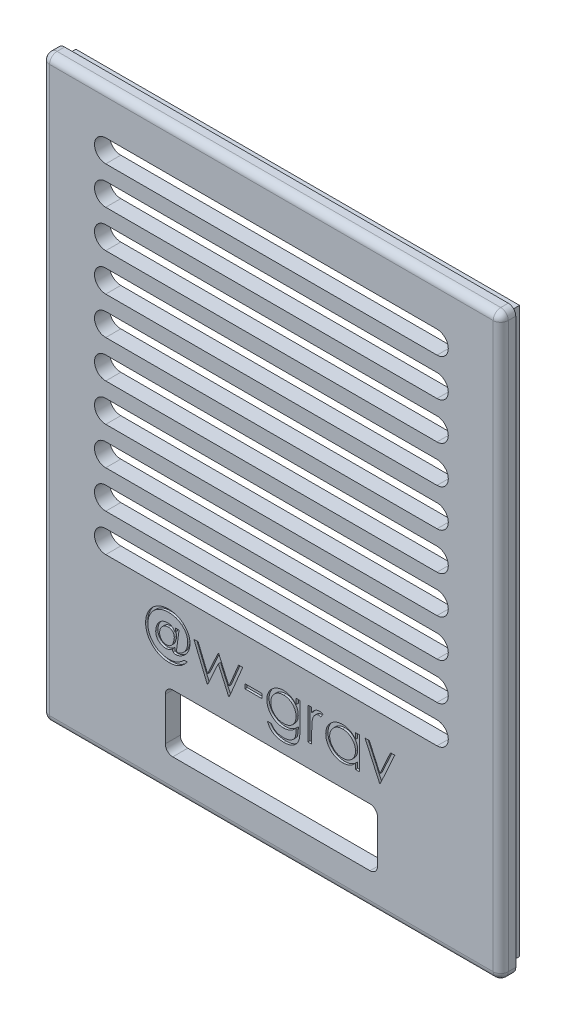
SolidWorks part; units mm, degrees
ref_plane "Спереди" through (0, 0, 0) normal (0, 0, 1) x (1, 0, 0)
ref_plane "Сверху" through (0, 0, 0) normal (0, 1, 0) x (1, 0, 0)
ref_plane "Справа" through (0, 0, 0) normal (1, 0, 0) x (0, 0, -1)
sketch "Эскиз1" plane through (0, 0, 0) normal (0, 0, 1) x (1, 0, 0)
  line L0 (-29.5, -37.5) -> (29.5, -37.5)
  line L1 (-29.5, -37.5) -> (-29.5, 37.5)
  line L2 (-29.5, 37.5) -> (29.5, 37.5)
  line L3 (29.5, -37.5) -> (29.5, 37.5)
  line L4 (-29.5, -37.5) -> (29.5, 37.5) construction
  line L5 (-29.5, 37.5) -> (29.5, -37.5) construction
  point P0 (0, 0)
extrude "Бобышка-Вытянуть1" add sketch "Эскиз1" along normal blind 2
sketch "Эскиз2" plane through (0, 0, 2) normal (0, 0, 1) x (1, 0, 0)
  line L1 (-29.5, -37.5) -> (29.5, -37.5)
  line L2 (-29.5, -37.5) -> (-29.5, 37.5)
  line L3 (-29.5, 37.5) -> (29.5, 37.5)
  line L4 (29.5, -37.5) -> (29.5, 37.5)
  line L5 (-29.5, -37.5) -> (29.5, 37.5) construction
  line L6 (-29.5, 37.5) -> (29.5, -37.5) construction
  point P0 (0, 0)
extrude "Вытянуть-Тонкостенный1" add sketch "Эскиз2" against normal blind 2 thin
fillet "Скругление1" radius 1 4 edges at (-30.5, -38.5, 1) (30.5, -38.5, 1) (30.5, 38.5, 1) (-30.5, 38.5, 1)
sketch "Эскиз5" plane through (0, 0, 0) normal (0, 0, -1) x (-1, 0, 0)
  line L1 (-29.5, 37.5) -> (29.5, 37.5)
  line L2 (-29.5, 37.5) -> (-29.5, -37.5)
  line L3 (-29.5, -37.5) -> (29.5, -37.5)
  line L4 (29.5, 37.5) -> (29.5, -37.5)
  point P6 (0, 0)
  point P7 (0, 0)
extrude "Вытянуть-Тонкостенный2" add sketch "Эскиз5" along normal blind 1.5 and the other way blind 1 thin
fillet "Скругление2" radius 1 8 edges at (-30.2071, 38.2071, 2) (0, 38.5, 2) (30.2071, 38.2071, 2) (30.5, 0, 2) (30.2071, -38.2071, 2) (0, -38.5, 2) (-30.2071, -38.2071, 2) (-30.5, 0, 2)
sketch "Эскиз6" plane through (0, 0, 0) normal (0, 0, -1) x (-1, 0, 0)
  line L0 (-22.0278, 31.2773) -> (22.0278, 31.2773) construction
  line L1 (-22.0278, 32.7744) -> (22.0278, 32.7744)
  line L2 (-22.0278, 29.7803) -> (22.0278, 29.7803)
  line L3 (-22.0278, 26.2773) -> (22.0278, 26.2773) construction
  line L4 (-22.0278, 27.7744) -> (22.0278, 27.7744)
  line L5 (-22.0278, 24.7803) -> (22.0278, 24.7803)
  line L6 (-22.0278, 21.2773) -> (22.0278, 21.2773) construction
  line L7 (-22.0278, 22.7744) -> (22.0278, 22.7744)
  line L8 (-22.0278, 19.7803) -> (22.0278, 19.7803)
  line L9 (-22.0278, 16.2773) -> (22.0278, 16.2773) construction
  line L10 (-22.0278, 17.7744) -> (22.0278, 17.7744)
  line L11 (-22.0278, 14.7803) -> (22.0278, 14.7803)
  line L12 (-22.0278, 11.2773) -> (22.0278, 11.2773) construction
  line L13 (-22.0278, 12.7744) -> (22.0278, 12.7744)
  line L14 (-22.0278, 9.7803) -> (22.0278, 9.7803)
  line L15 (-22.0278, 6.2773) -> (22.0278, 6.2773) construction
  line L16 (-22.0278, 7.7744) -> (22.0278, 7.7744)
  line L17 (-22.0278, 4.7803) -> (22.0278, 4.7803)
  line L18 (-22.0278, 1.2773) -> (22.0278, 1.2773) construction
  line L19 (-22.0278, 2.7744) -> (22.0278, 2.7744)
  line L20 (-22.0278, -0.2197) -> (22.0278, -0.2197)
  line L21 (-22.0278, -3.7227) -> (22.0278, -3.7227) construction
  line L22 (-22.0278, -2.2256) -> (22.0278, -2.2256)
  line L23 (-22.0278, -5.2197) -> (22.0278, -5.2197)
  line L24 (-22.0278, -8.7227) -> (22.0278, -8.7227) construction
  line L25 (-22.0278, -7.2256) -> (22.0278, -7.2256)
  line L26 (-22.0278, -10.2197) -> (22.0278, -10.2197)
  line L27 (-22.0278, -13.7227) -> (22.0278, -13.7227) construction
  line L28 (-22.0278, -12.2256) -> (22.0278, -12.2256)
  line L29 (-22.0278, -15.2197) -> (22.0278, -15.2197)
  line L31 (-13.1149, -34.0575) -> (13.1149, -34.0575)
  line L32 (-14.1149, -33.0575) -> (-14.1149, -27.3585)
  line L33 (-13.1149, -26.3585) -> (13.1149, -26.3585)
  line L34 (14.1149, -33.0575) -> (14.1149, -27.3585)
  line L35 (-14.1149, -34.0575) -> (14.1149, -26.3585) construction
  line L36 (-14.1149, -26.3585) -> (14.1149, -34.0575) construction
  arc A0 (-22.0278, 32.7744) -> (-22.0278, 29.7803) centre (-22.0278, 31.2773) ccw
  arc A1 (22.0278, 29.7803) -> (22.0278, 32.7744) centre (22.0278, 31.2773) ccw
  arc A2 (-22.0278, 27.7744) -> (-22.0278, 24.7803) centre (-22.0278, 26.2773) ccw
  arc A3 (22.0278, 24.7803) -> (22.0278, 27.7744) centre (22.0278, 26.2773) ccw
  arc A4 (-22.0278, 22.7744) -> (-22.0278, 19.7803) centre (-22.0278, 21.2773) ccw
  arc A5 (22.0278, 19.7803) -> (22.0278, 22.7744) centre (22.0278, 21.2773) ccw
  arc A6 (-22.0278, 17.7744) -> (-22.0278, 14.7803) centre (-22.0278, 16.2773) ccw
  arc A7 (22.0278, 14.7803) -> (22.0278, 17.7744) centre (22.0278, 16.2773) ccw
  arc A8 (-22.0278, 12.7744) -> (-22.0278, 9.7803) centre (-22.0278, 11.2773) ccw
  arc A9 (22.0278, 9.7803) -> (22.0278, 12.7744) centre (22.0278, 11.2773) ccw
  arc A10 (-22.0278, 7.7744) -> (-22.0278, 4.7803) centre (-22.0278, 6.2773) ccw
  arc A11 (22.0278, 4.7803) -> (22.0278, 7.7744) centre (22.0278, 6.2773) ccw
  arc A12 (-22.0278, 2.7744) -> (-22.0278, -0.2197) centre (-22.0278, 1.2773) ccw
  arc A13 (22.0278, -0.2197) -> (22.0278, 2.7744) centre (22.0278, 1.2773) ccw
  arc A14 (-22.0278, -2.2256) -> (-22.0278, -5.2197) centre (-22.0278, -3.7227) ccw
  arc A15 (22.0278, -5.2197) -> (22.0278, -2.2256) centre (22.0278, -3.7227) ccw
  arc A16 (-22.0278, -7.2256) -> (-22.0278, -10.2197) centre (-22.0278, -8.7227) ccw
  arc A17 (22.0278, -10.2197) -> (22.0278, -7.2256) centre (22.0278, -8.7227) ccw
  arc A18 (-22.0278, -12.2256) -> (-22.0278, -15.2197) centre (-22.0278, -13.7227) ccw
  arc A19 (22.0278, -15.2197) -> (22.0278, -12.2256) centre (22.0278, -13.7227) ccw
  arc A20 (-13.1149, -34.0575) -> (-14.1149, -33.0575) centre (-13.1149, -33.0575) cw
  arc A21 (13.1149, -34.0575) -> (14.1149, -33.0575) centre (13.1149, -33.0575) ccw
  arc A22 (14.1149, -27.3585) -> (13.1149, -26.3585) centre (13.1149, -27.3585) ccw
  arc A23 (-13.1149, -26.3585) -> (-14.1149, -27.3585) centre (-13.1149, -27.3585) ccw
  point P2 (0, 31.2773)
  point P7 (0, -30.208)
  point P11 (0, 26.2773)
  point P18 (0, 21.2773)
  point P25 (0, 16.2773)
  point P32 (0, 11.2773)
  point P39 (0, 6.2773)
  point P46 (0, 1.2773)
  point P53 (0, -3.7227)
  point P60 (0, -8.7227)
  point P67 (0, -13.7227)
  dimension "D2" = 1
  dimension "D1" = 10
extrude "Вырез-Вытянуть1" cut sketch "Эскиз6" against normal up to next
sketch "Эскиз7" plane through (0, 0, 2) normal (0, 0, 1) x (1, 0, 0)
  text T0 "@w-grav" font "Century Gothic" height in points 22
extrude "Вырез-Вытянуть2" cut sketch "Эскиз7" against normal blind 0.3
